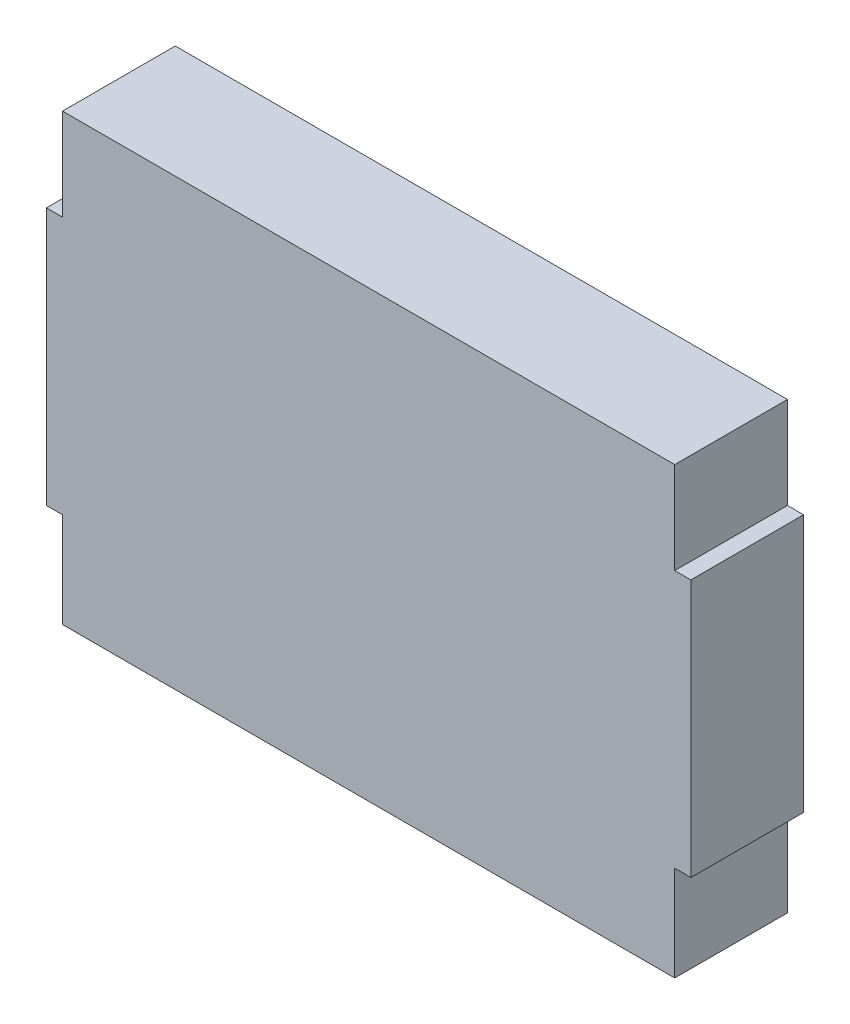
SolidWorks part; units mm, degrees
ref_plane "前视基准面" through (0, 0, 0) normal (0, 0, 1) x (1, 0, 0)
ref_plane "上视基准面" through (0, 0, 0) normal (0, 1, 0) x (1, 0, 0)
ref_plane "右视基准面" through (0, 0, 0) normal (1, 0, 0) x (0, 0, -1)
sketch "草图1" plane through (0, 0, 0) normal (0, 0, 1) x (1, 0, 0)
  line L0 (-4.755, -3.456) -> (-4.755, -1.981)
  line L1 (-4.755, -1.981) -> (-5.005, -1.981)
  line L2 (-5.005, -1.981) -> (-5.005, 2.019)
  line L3 (-5.005, 2.019) -> (-4.755, 2.019)
  line L4 (-4.755, 2.019) -> (-4.755, 3.444)
  line L5 (-4.755, 3.444) -> (4.745, 3.444)
  line L6 (4.745, 3.444) -> (4.745, 2.019)
  line L7 (4.745, 2.019) -> (4.995, 2.019)
  line L8 (4.995, 2.019) -> (4.995, -1.981)
  line L9 (4.995, -1.981) -> (4.745, -1.981)
  line L10 (4.745, -1.981) -> (4.745, -3.456)
  line L11 (4.745, -3.456) -> (-4.755, -3.456)
extrude "Component_Outline" add sketch "草图1" along normal blind 1.75 separate body
sketch3d "3D草图1"
  line L0 (0, 0, 0) -> (1, 0, 0)
  line L1 (0, 0, 0) -> (0, 1, 0)
  line L2 (0, 0, 0) -> (0, 0, 1)
  point P0 (0, 0, 0)
